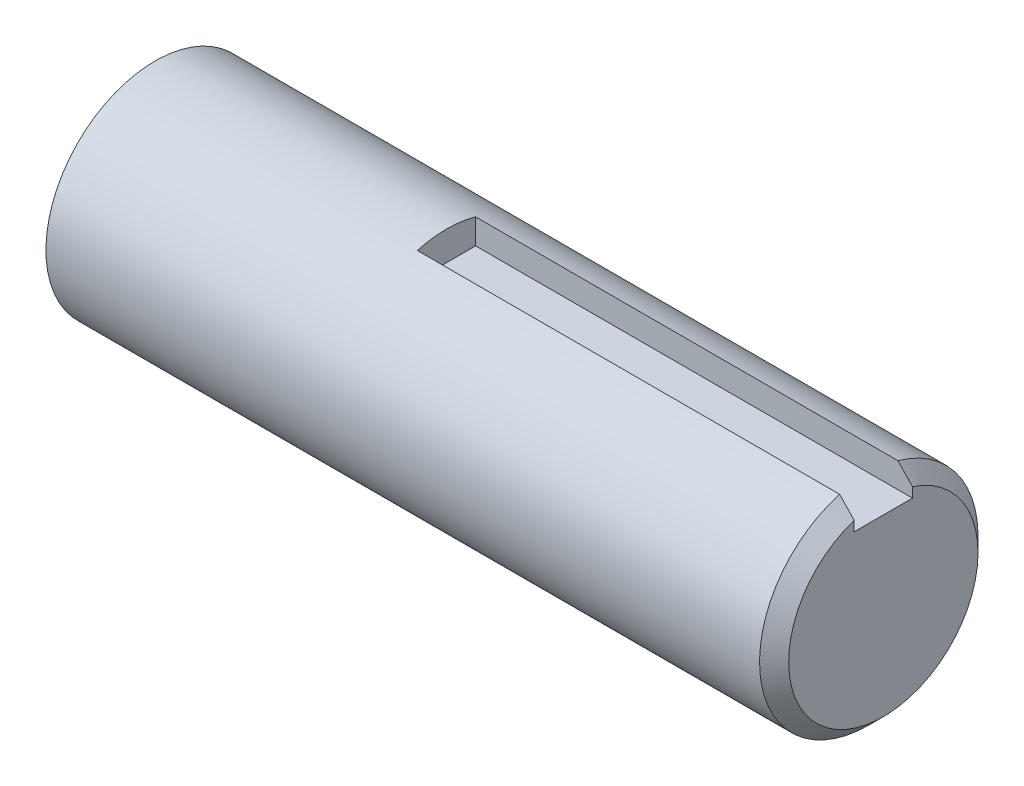
SolidWorks part; units mm, degrees
ref_plane "Front Plane" through (0, 0, 0) normal (0, 0, 1) x (1, 0, 0)
ref_plane "Top Plane" through (0, 0, 0) normal (0, 1, 0) x (1, 0, 0)
ref_plane "Right Plane" through (0, 0, 0) normal (1, 0, 0) x (0, 0, -1)
sketch "Sketch1" plane through (0, 0, 0) normal (1, 0, 0) x (0, 0, -1)
  circle A0 centre (0, 0) radius 15
  dimension "D1" = 30
extrude "Boss-Extrude1" add sketch "Sketch1" along normal mid plane 100
sketch "Sketch2" plane through (50, 0, 0) normal (1, 0, 0) x (0, 0, -1)
  line L0 (0, 0) -> (0, 15) construction
  line L1 (-4, 11) -> (4, 11)
  line L2 (-4, 11) -> (-4, 14.4568)
  line L4 (4, 11) -> (4, 14.4568)
  line L5 (-4, 11) -> (4, 14.4568) construction
  line L6 (-4, 14.4568) -> (4, 11) construction
  circle A1 centre (0, 0) radius 15
  circle A2 centre (0, 0) radius 15
  point P0 (0, 12.7284)
  circle M7 centre (0, 0) radius 15
  dimension "D2" = 11
  dimension "D3" = 8
  dimension "D1" = 0
extrude "Cut-Extrude1" cut sketch "Sketch2" against normal blind 60 contours L1 L4 L2 M7
chamfer "Chamfer1" distance 2 angle 45 1 edges at (50, -15, 0)
